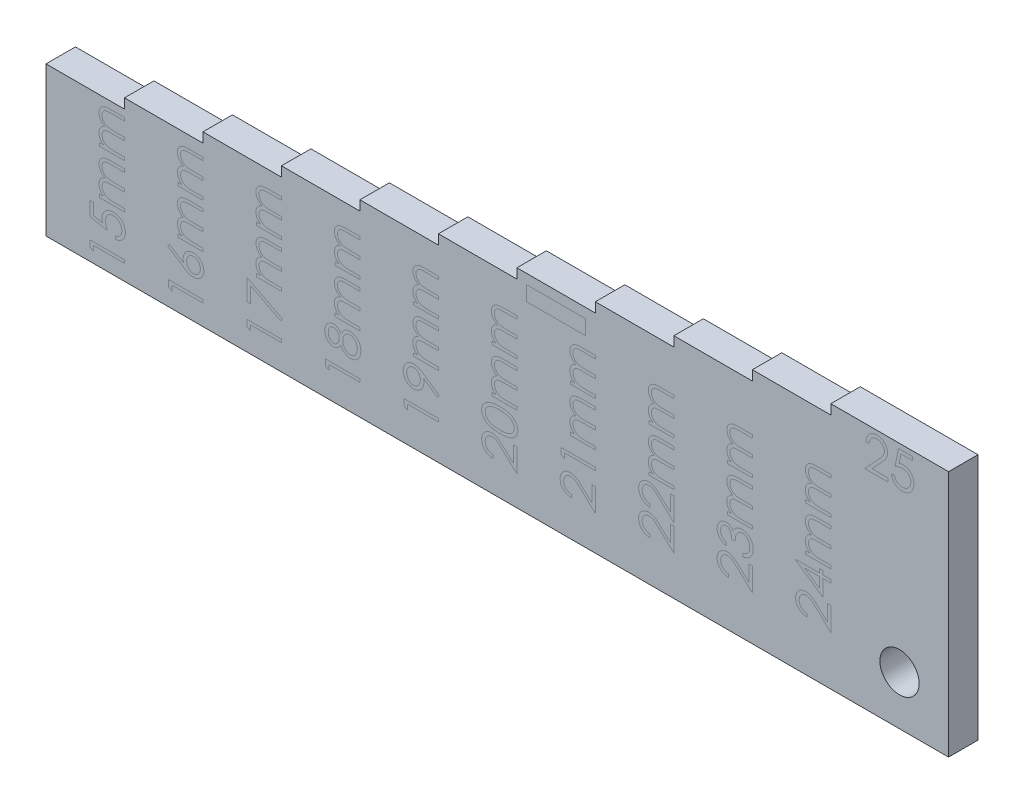
SolidWorks part; units mm, degrees
ref_plane "Front Plane" through (0, 0, 0) normal (0, 0, 1) x (1, 0, 0)
ref_plane "Top Plane" through (0, 0, 0) normal (0, 1, 0) x (1, 0, 0)
ref_plane "Right Plane" through (0, 0, 0) normal (1, 0, 0) x (0, 0, -1)
sketch "Sketch1" plane through (0, 0, 0) normal (0, 0, 1) x (1, 0, 0)
  line L0 (0, 0) -> (0, 25.2)
  line L1 (0, 25.2) -> (-12, 25.2)
  line L2 (-12, 25.2) -> (-12, 24.2)
  line L3 (-12, 24.2) -> (-20, 24.2)
  line L4 (-20, 24.2) -> (-20, 23.2)
  line L5 (-20, 23.2) -> (-28, 23.2)
  line L6 (-28, 23.2) -> (-28, 22.2)
  line L7 (-28, 22.2) -> (-36, 22.2)
  line L8 (-36, 22.2) -> (-36, 21.2)
  line L9 (-36, 21.2) -> (-44, 21.2)
  line L10 (-44, 21.2) -> (-44, 20.2)
  line L11 (-44, 20.2) -> (-52, 20.2)
  line L12 (-52, 20.2) -> (-52, 19.2)
  line L13 (-52, 19.2) -> (-60, 19.2)
  line L14 (-60, 19.2) -> (-60, 18.2)
  line L15 (-60, 18.2) -> (-68, 18.2)
  line L16 (-68, 18.2) -> (-68, 17.2)
  line L17 (-68, 17.2) -> (-76, 17.2)
  line L18 (-76, 17.2) -> (-76, 16.2)
  line L19 (-76, 16.2) -> (-84, 16.2)
  line L20 (-84, 16.2) -> (-84, 15.2)
  line L21 (-84, 15.2) -> (-92, 15.2)
  line L22 (-92, 15.2) -> (-92, 0)
  line L23 (-92, 0) -> (0, 0)
  line L24 (-5, 5) -> (0, 5) construction
  line L25 (-5, 5) -> (-5, 0) construction
  circle A0 centre (-5, 5) radius 2
  dimension "D5" = 5
  dimension "D6" = 4
  dimension "D1" = 12
  dimension "D2" = 25.2
  dimension "D3" = 1
  dimension "D4" = 8
  dimension "D7" = 5
extrude "Boss-Extrude1" add sketch "Sketch1" along normal blind 3
sketch "Sketch2" plane through (0, 0, 3) normal (0, 0, 1) x (1, 0, 0)
  line L0 (-84, 15.2) -> (-84, 0) construction
  line L1 (-92, 0) -> (0, 0) construction
  line L2 (-76, 16.2) -> (-76, 0) construction
  line L3 (-68, 17.2) -> (-68, 0) construction
  line L4 (-60, 18.2) -> (-60, 0) construction
  line L5 (-52, 19.2) -> (-52, 0) construction
  line L6 (-44, 20.2) -> (-44, 0) construction
  line L7 (-36, 21.2) -> (-36, 0) construction
  line L8 (-28, 22.2) -> (-28, 0) construction
  line L9 (-20, 23.2) -> (-20, 0) construction
  line L10 (-12, 24.2) -> (-12, 0) construction
  line L11 (-12, 21.2) -> (0, 21.2) construction
  line L12 (0, 0) -> (0, 25.2) construction
  line L13 (-36, 21.2) -> (-44, 21.2) construction
  line L14 (-43, 20.2) -> (-37, 20.2)
  line L15 (-43, 20.2) -> (-43, 18.7)
  line L16 (-43, 18.7) -> (-37, 18.7)
  line L17 (-37, 20.2) -> (-37, 18.7)
  text T0 "25"
  text T1 "24mm"
  text T2 "23mm"
  text T3 "22mm"
  text T4 "21mm"
  text T5 "20mm"
  text T6 "19mm"
  text T7 "18mm"
  text T8 "17mm"
  text T9 "16mm"
  text T10 "15mm"
  dimension "D1" = 1
  dimension "D2" = 1
  dimension "D3" = 1
  dimension "D4" = 1.5
split line "Split Line1"
